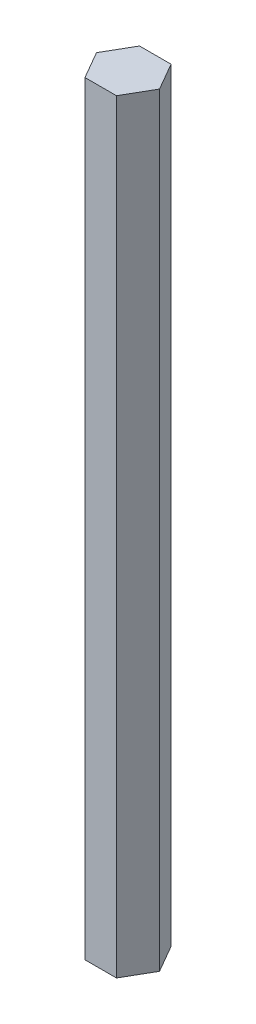
SolidWorks part; units mm, degrees
ref_plane "Front Plane" through (0, 0, 0) normal (0, 0, 1) x (1, 0, 0)
ref_plane "Top Plane" through (0, 0, 0) normal (0, 1, 0) x (1, 0, 0)
ref_plane "Right Plane" through (0, 0, 0) normal (1, 0, 0) x (0, 0, -1)
sketch "Sketch1" plane through (0, 0, 0) normal (0, 1, 0) x (1, 0, 0)
  line L1 (-7.3323, 0) -> (-3.6662, -6.35)
  line L2 (-3.6662, -6.35) -> (3.6662, -6.35)
  line L3 (3.6662, -6.35) -> (7.3323, 0)
  line L4 (7.3323, 0) -> (3.6662, 6.35)
  line L5 (3.6662, 6.35) -> (-3.6662, 6.35)
  line L6 (-3.6662, 6.35) -> (-7.3323, 0)
  circle A0 centre (0, 0) radius 6.35 construction
  dimension "D1" = 12.7
extrude "Boss-Extrude1" add sketch "Sketch1" along normal blind 177.8
